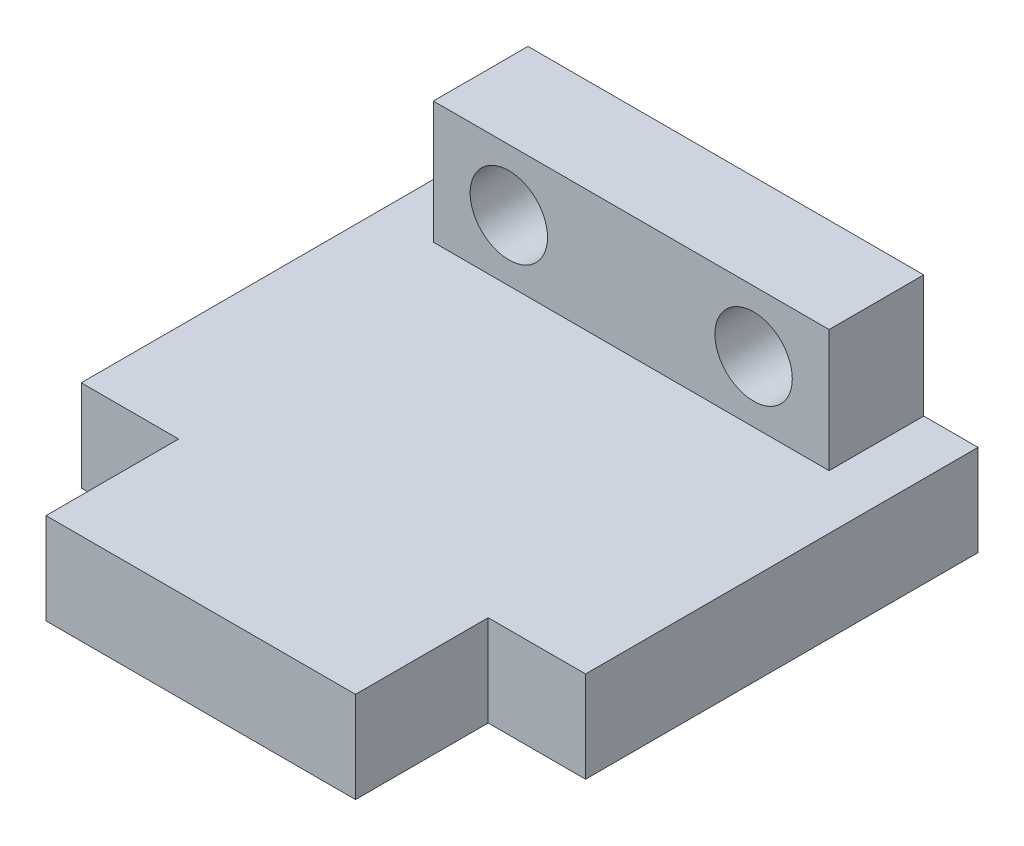
SolidWorks part; units mm, degrees
ref_plane "前视基准面" through (0, 0, 0) normal (0, 0, 1) x (1, 0, 0)
ref_plane "上视基准面" through (0, 0, 0) normal (0, 1, 0) x (1, 0, 0)
ref_plane "右视基准面" through (0, 0, 0) normal (1, 0, 0) x (0, 0, -1)
other "Configuration Table"
sketch "草图1" plane through (0, 0, 0) normal (0, 1, 0) x (1, 0, 0)
  line L1 (-11.405, -8.875) -> (11.405, -8.875)
  line L2 (-11.405, -8.875) -> (-11.405, 8.875)
  line L3 (-11.405, 8.875) -> (11.405, 8.875)
  line L4 (11.405, -8.875) -> (11.405, 8.875)
  line L5 (-11.405, -8.875) -> (11.405, 8.875) construction
  line L6 (-11.405, 8.875) -> (11.405, -8.875) construction
  point P0 (0, 0)
  dimension "D1" = 22.81
  dimension "D2" = 17.75
extrude "凸台-拉伸1" add sketch "草图1" along normal blind 1.06
sketch "草图2" plane through (0, 0, -8.875) normal (0, 0, -1) x (-1, 0, 0)
  line L1 (11.405, 1.06) -> (9.965, 1.06)
  line L2 (11.405, 1.06) -> (11.405, -3.065)
  line L3 (11.405, -3.065) -> (9.965, -3.065)
  line L4 (-11.405, 0) -> (11.405, 0)
  line L5 (11.405, 0) -> (11.405, 1.06)
  line L6 (11.405, 1.06) -> (-11.405, 1.06)
  line L7 (-11.405, 1.06) -> (-11.405, 0)
  line L8 (-11.405, 0) -> (11.405, 0)
  line L9 (11.405, 0) -> (11.405, 1.06)
  line L10 (11.405, 1.06) -> (-11.405, 1.06)
  line L11 (-11.405, 1.06) -> (-11.405, 0)
  line L12 (9.965, 1.06) -> (9.965, -3.065)
  line L13 (-11.405, 1.06) -> (-9.965, 1.06)
  line L14 (-11.405, 1.06) -> (-11.405, -3.065)
  line L15 (-11.405, -3.065) -> (-9.965, -3.065)
  line L16 (-9.965, 1.06) -> (-9.965, -3.065)
  line M10 (-11.405, 0) -> (11.405, 0)
  dimension "D2" = 1.44
  dimension "D3" = 1.44
  dimension "D1" = 0
extrude "凸台-拉伸2" add sketch "草图2" against normal blind 6.92 contours L16 L14 L15 M10 | L8 L12 L3 L2
sketch "草图3" plane through (0, 0, 0) normal (0, -1, 0) x (1, 0, 0)
  line L1 (-11.405, -1.955) -> (11.405, -1.955)
  line L2 (-11.405, -1.955) -> (-11.405, 8.875)
  line L3 (-11.405, 8.875) -> (11.405, 8.875)
  line L4 (11.405, -1.955) -> (11.405, 8.875)
  line L8 (-9.965, -1.955) -> (-9.965, -8.875)
  line L9 (-9.965, -8.875) -> (9.965, -8.875)
  line L10 (9.965, -8.875) -> (9.965, -1.955)
  line L11 (9.965, -1.955) -> (11.405, -1.955)
  line L12 (11.405, -1.955) -> (11.405, 8.875)
  line L13 (11.405, 8.875) -> (-11.405, 8.875)
  line L14 (-11.405, 8.875) -> (-11.405, -1.955)
  line L15 (-11.405, -1.955) -> (-9.965, -1.955)
  line L16 (-9.965, -1.955) -> (-9.965, -8.875)
  line L17 (-9.965, -8.875) -> (9.965, -8.875)
  line L18 (9.965, -8.875) -> (9.965, -1.955)
  line L19 (9.965, -1.955) -> (11.405, -1.955)
  line L20 (11.405, -1.955) -> (11.405, 8.875)
  line L21 (11.405, 8.875) -> (-11.405, 8.875)
  line L22 (-11.405, 8.875) -> (-11.405, -1.955)
  line L23 (-11.405, -1.955) -> (-9.965, -1.955)
  line M12 (9.965, -1.955) -> (11.405, -1.955)
  line M13 (11.405, -1.955) -> (11.405, 8.875)
  line M14 (11.405, 8.875) -> (-11.405, 8.875)
  line M15 (-11.405, 8.875) -> (-11.405, -1.955)
  line M16 (-11.405, -1.955) -> (-9.965, -1.955)
  dimension "D1" = 0
extrude "凸台-拉伸3" add sketch "草图3" along normal up to surface (3.065 mm away) contours L1 M16 M12 M13 M14 M15 up to face at (10.685, -3.065, -5.415)
sketch "草图4" plane through (0, -3.065, 0) normal (0, -1, 0) x (1, 0, 0)
  line L0 (-4.93, 0.825) -> (-4.93, -1.955)
  line L1 (-7.855, 3.75) -> (-11.405, 3.75)
  line L2 (0, -1.955) -> (0, 8.875)
  line L8 (9.965, -8.875) -> (11.405, -8.875)
  line L9 (11.405, -8.875) -> (11.405, 8.875)
  line L10 (11.405, 8.875) -> (-11.405, 8.875)
  line L11 (-11.405, 8.875) -> (-11.405, -8.875)
  line L12 (-11.405, -8.875) -> (-9.965, -8.875)
  line L13 (-9.965, -8.875) -> (-9.965, -1.955)
  line L14 (-9.965, -1.955) -> (9.965, -1.955)
  line L15 (9.965, -1.955) -> (9.965, -8.875)
  line L16 (9.965, -8.875) -> (11.405, -8.875)
  line L17 (11.405, -8.875) -> (11.405, 8.875)
  line L18 (11.405, 8.875) -> (-11.405, 8.875)
  line L19 (-11.405, 8.875) -> (-11.405, -8.875)
  line L20 (-11.405, -8.875) -> (-9.965, -8.875)
  line L21 (-9.965, -8.875) -> (-9.965, -1.955)
  line L22 (-9.965, -1.955) -> (9.965, -1.955)
  line L23 (9.965, -1.955) -> (9.965, -8.875)
  circle A0 centre (-4.93, 3.75) radius 2.925
  circle A1 centre (4.93, 3.75) radius 2.925
  line M14 (11.405, 8.875) -> (-11.405, 8.875)
  dimension "D2" = 5.85
  dimension "D3" = 2.78
  dimension "D4" = 3.55
  dimension "D1" = 0
extrude "凸台-拉伸4" add sketch "草图4" along normal blind 5.85 contours A1 | A0 M14
sketch "草图5" plane through (0, 1.06, 0) normal (0, 1, 0) x (1, 0, 0)
  line L1 (-11.405, 8.875) -> (11.405, 8.875)
  line L2 (-11.405, 8.875) -> (-11.405, 4.595)
  line L3 (-11.405, 4.595) -> (11.405, 4.595)
  line L4 (11.405, -8.875) -> (11.405, 8.875)
  line L5 (11.405, 8.875) -> (-11.405, 8.875)
  line L6 (-11.405, 8.875) -> (-11.405, -8.875)
  line L7 (-11.405, -8.875) -> (11.405, -8.875)
  line L8 (11.405, -8.875) -> (11.405, 8.875)
  line L9 (11.405, 8.875) -> (-11.405, 8.875)
  line L10 (-11.405, 8.875) -> (-11.405, -8.875)
  line L11 (-11.405, -8.875) -> (11.405, -8.875)
  line L12 (11.405, 8.875) -> (11.405, 4.595)
  line M6 (11.405, -8.875) -> (11.405, 8.875)
  line M7 (11.405, 8.875) -> (-11.405, 8.875)
  line M8 (-11.405, 8.875) -> (-11.405, -8.875)
  dimension "D2" = 4.28
  dimension "D1" = 0
extrude "凸台-拉伸5" add sketch "草图5" along normal blind 5.53 contours L3 M8 M6 M7
sketch "草图6" plane through (0, 0, -4.595) normal (0, 0, 1) x (1, 0, 0)
  line L0 (11.405, 3.825) -> (5.535, 3.825)
  line L1 (0, 1.06) -> (0, 6.59)
  line L4 (-11.405, 1.06) -> (11.405, 1.06)
  line L5 (11.405, 1.06) -> (11.405, 6.59)
  line L6 (11.405, 6.59) -> (-11.405, 6.59)
  line L7 (-11.405, 6.59) -> (-11.405, 1.06)
  line L8 (-11.405, 1.06) -> (11.405, 1.06)
  line L9 (11.405, 1.06) -> (11.405, 6.59)
  line L10 (11.405, 6.59) -> (-11.405, 6.59)
  line L11 (-11.405, 6.59) -> (-11.405, 1.06)
  circle A0 centre (5.535, 3.825) radius 1.75
  circle A1 centre (-5.535, 3.825) radius 1.75
  dimension "D3" = 3.5
  dimension "D2" = 5.87
  dimension "D1" = 0
extrude "切除-拉伸1" cut sketch "草图6" against normal blind 5.53
sketch "草图7" plane through (0, 1.06, 0) normal (0, 1, 0) x (1, 0, 0)
  line L1 (-7, -14.875) -> (7, -14.875)
  line L2 (-7, -14.875) -> (-7, -2.875)
  line L3 (-7, -2.875) -> (7, -2.875)
  line L4 (11.405, 4.595) -> (-11.405, 4.595)
  line L5 (-11.405, 4.595) -> (-11.405, -8.875)
  line L6 (-11.405, -8.875) -> (11.405, -8.875)
  line L7 (11.405, -8.875) -> (11.405, 4.595)
  line L8 (11.405, 4.595) -> (-11.405, 4.595)
  line L9 (-11.405, 4.595) -> (-11.405, -8.875)
  line L10 (-11.405, -8.875) -> (11.405, -8.875)
  line L11 (11.405, -8.875) -> (11.405, 4.595)
  line L12 (7, -14.875) -> (7, -2.875)
  line L13 (-7, -14.875) -> (7, -2.875) construction
  line L14 (-7, -2.875) -> (7, -14.875) construction
  point P2 (0, -8.875)
  line M9 (-11.405, -8.875) -> (11.405, -8.875)
  dimension "D2" = 14
  dimension "D3" = 12
  dimension "D1" = 0
extrude "凸台-拉伸6" add sketch "草图7" against normal up to surface (4.125 mm away) contours L1 L12 L2 M9 up to face at (-4.93, -3.065, 0.825)
sketch "草图8" plane through (0, -8.915, 0) normal (0, -1, 0) x (1, 0, 0)
  circle A1 centre (-4.93, 3.75) radius 2.925
  circle A2 centre (-4.93, 3.75) radius 2.925
  circle A3 centre (4.93, 3.75) radius 2.925
  circle A4 centre (4.93, 3.75) radius 2.925
  dimension "D1" = 0
  dimension "D2" = 0
extrude "切除-拉伸2" cut sketch "草图8" against normal blind 4
sketch "草图9" plane through (0, -4.915, 0) normal (0, -1, 0) x (1, 0, 0)
  line L0 (-4.93, 3.75) -> (-2.005, 3.75)
  line L1 (-2.005, 3.75) -> (-2.005, 6.675)
  line L2 (-2.005, 6.675) -> (-4.93, 6.675)
  line L3 (4.93, 3.75) -> (4.93, 6.675)
  line L4 (4.93, 6.675) -> (2.005, 6.675)
  line L5 (2.005, 6.675) -> (2.005, 3.75)
  line L7 (-7.855, 0.825) -> (-2.005, 0.825)
  line L8 (-7.855, 0.825) -> (-7.855, 6.675)
  line L9 (-7.855, 6.675) -> (-2.005, 6.675)
  line L10 (-2.005, 0.825) -> (-2.005, 6.675)
  line L11 (-7.855, 0.825) -> (-2.005, 6.675) construction
  line L12 (-7.855, 6.675) -> (-2.005, 0.825) construction
  line L13 (7.855, 0.825) -> (2.005, 0.825)
  line L14 (7.855, 0.825) -> (7.855, 6.675)
  line L15 (7.855, 6.675) -> (2.005, 6.675)
  line L16 (2.005, 0.825) -> (2.005, 6.675)
  line L17 (7.855, 0.825) -> (2.005, 6.675) construction
  line L18 (7.855, 6.675) -> (2.005, 0.825) construction
  circle A1 centre (-4.93, 3.75) radius 2.925
  circle A2 centre (-4.93, 3.75) radius 2.925
  circle A3 centre (4.93, 3.75) radius 2.925
  circle A4 centre (4.93, 3.75) radius 2.925
  circle M3 centre (-4.93, 3.75) radius 2.925
  dimension "D1" = 0
  dimension "D2" = 0
extrude "凸台-拉伸7" add sketch "草图9" against normal up to surface (1.85 mm away) contours L9 L8 M3 | L8 L7 M3 | L7 L10 M3 | L1 L2 M3 | A4 L4 L5 | A4 L16 L13 | A4 L13 L14 | A4 L14 L15 up to face at (-4.93, -3.065, 0.825)
sketch "草图10" plane through (0, 6.59, 0) normal (0, 1, 0) x (1, 0, 0)
  line L0 (0, 8.875) -> (0, 4.595)
  line L2 (-8.95, 4.595) -> (8.95, 4.595)
  line L3 (-8.95, 4.595) -> (-8.95, 8.875)
  line L4 (-11.405, 8.875) -> (-11.405, 4.595)
  line L5 (-11.405, 4.595) -> (11.405, 4.595)
  line L6 (11.405, 4.595) -> (11.405, 8.875)
  line L7 (11.405, 8.875) -> (-11.405, 8.875)
  line L8 (-11.405, 8.875) -> (-11.405, 4.595)
  line L9 (-11.405, 4.595) -> (11.405, 4.595)
  line L10 (11.405, 4.595) -> (11.405, 8.875)
  line L11 (11.405, 8.875) -> (-11.405, 8.875)
  line L12 (-8.95, 8.875) -> (8.95, 8.875)
  line L13 (8.95, 4.595) -> (8.95, 8.875)
  line L14 (-8.95, 4.595) -> (8.95, 8.875) construction
  line L15 (-8.95, 8.875) -> (8.95, 4.595) construction
  point P6 (0, 6.735)
  line M5 (-11.405, 8.875) -> (-11.405, 4.595)
  line M6 (-11.405, 4.595) -> (11.405, 4.595)
  line M7 (11.405, 4.595) -> (11.405, 8.875)
  line M8 (11.405, 8.875) -> (-11.405, 8.875)
  dimension "D2" = 17.9
  dimension "D1" = 0
extrude "切除-拉伸3" cut sketch "草图10" against normal up to surface (5.53 mm away) contours L3 M6 M8 M5 | L13 M6 M7 M8 up to face at (0, 1.06, 7.0075)
